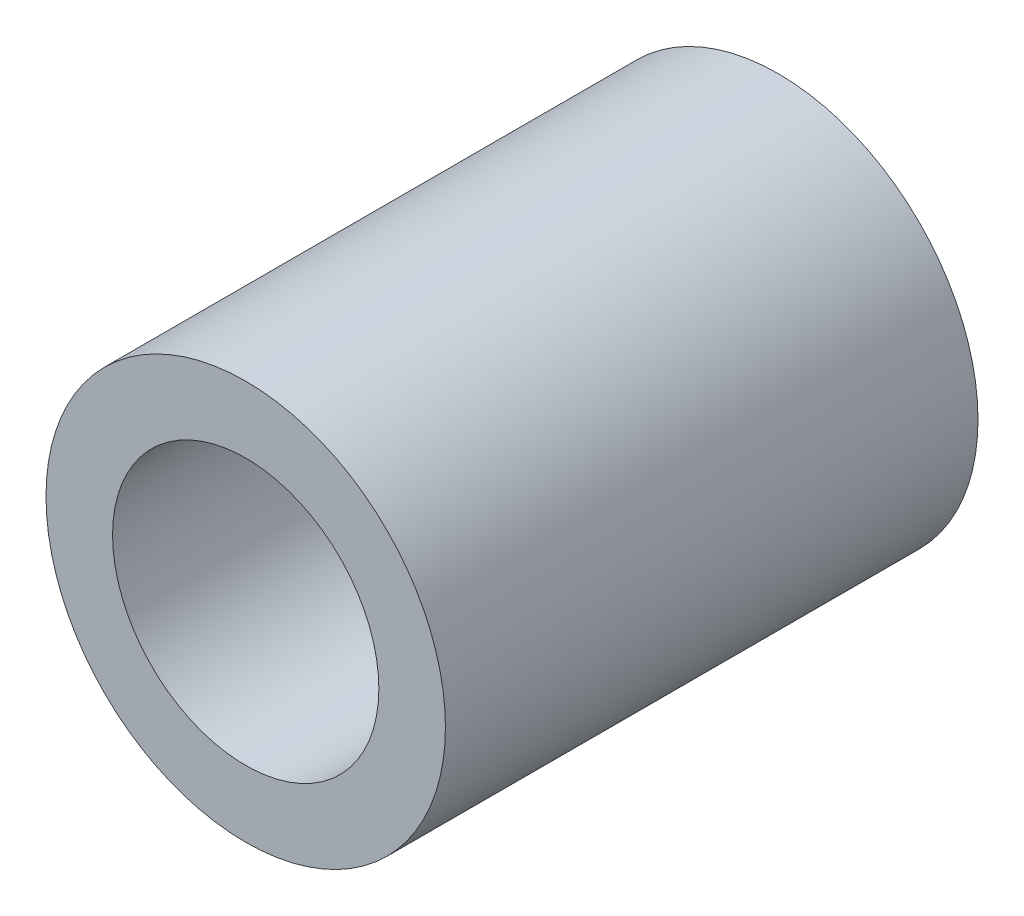
SolidWorks part; units mm, degrees
ref_plane "Front Plane" through (0, 0, 0) normal (0, 0, 1) x (1, 0, 0)
ref_plane "Top Plane" through (0, 0, 0) normal (0, 1, 0) x (1, 0, 0)
ref_plane "Right Plane" through (0, 0, 0) normal (1, 0, 0) x (0, 0, -1)
sketch "Sketch1" plane through (0, 0, 0) normal (0, 0, 1) x (1, 0, 0)
  circle A0 centre (0, 0) radius 19.05
extrude "Boss-Extrude1" add sketch "Sketch1" along normal blind 50.8
sketch "Sketch2" plane through (0, 0, 50.8) normal (0, 0, 1) x (1, 0, 0)
  circle A0 centre (0, 0) radius 12.7
extrude "Cut-Extrude1" cut sketch "Sketch2" against normal up to next
